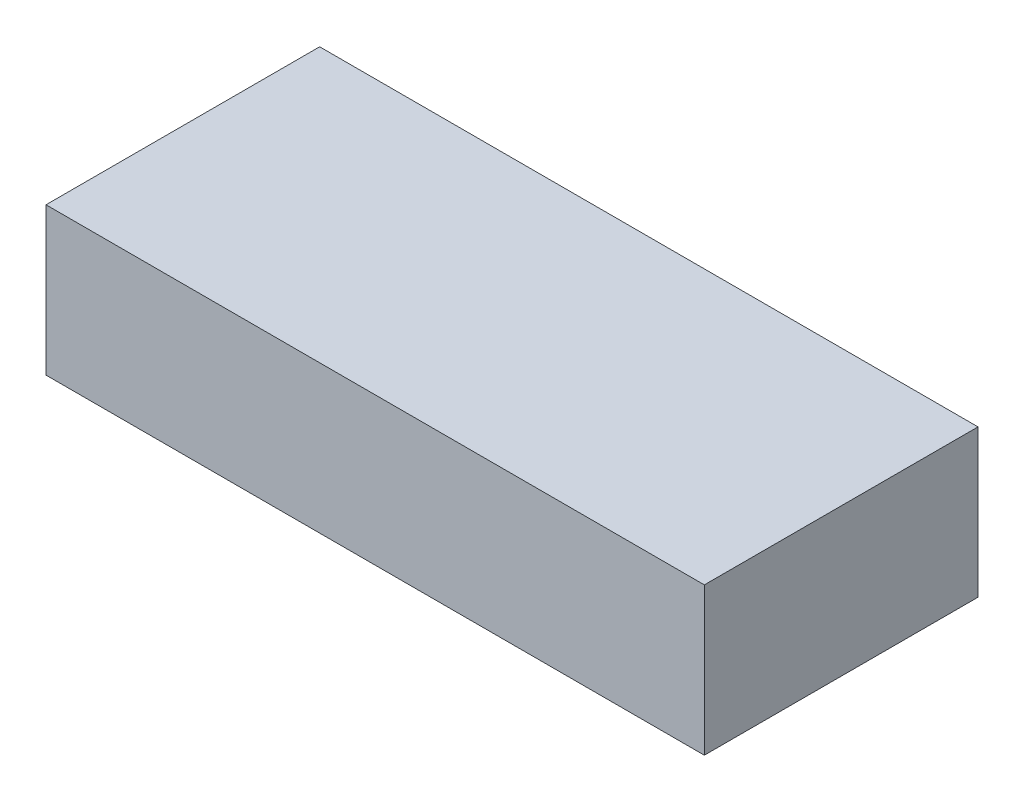
SolidWorks part; units mm, degrees
ref_plane "Front Plane" through (0, 0, 0) normal (0, 0, 1) x (1, 0, 0)
ref_plane "Top Plane" through (0, 0, 0) normal (0, 1, 0) x (1, 0, 0)
ref_plane "Right Plane" through (0, 0, 0) normal (1, 0, 0) x (0, 0, -1)
sketch "Sketch1" plane through (0, 0, 0) normal (0, 1, 0) x (1, 0, 0)
  line L1 (0, 0) -> (83, 0)
  line L2 (0, 0) -> (0, 34.5)
  line L3 (0, 34.5) -> (83, 34.5)
  line L4 (83, 0) -> (83, 34.5)
extrude "Boss-Extrude1" add sketch "Sketch1" along normal blind 18.6
